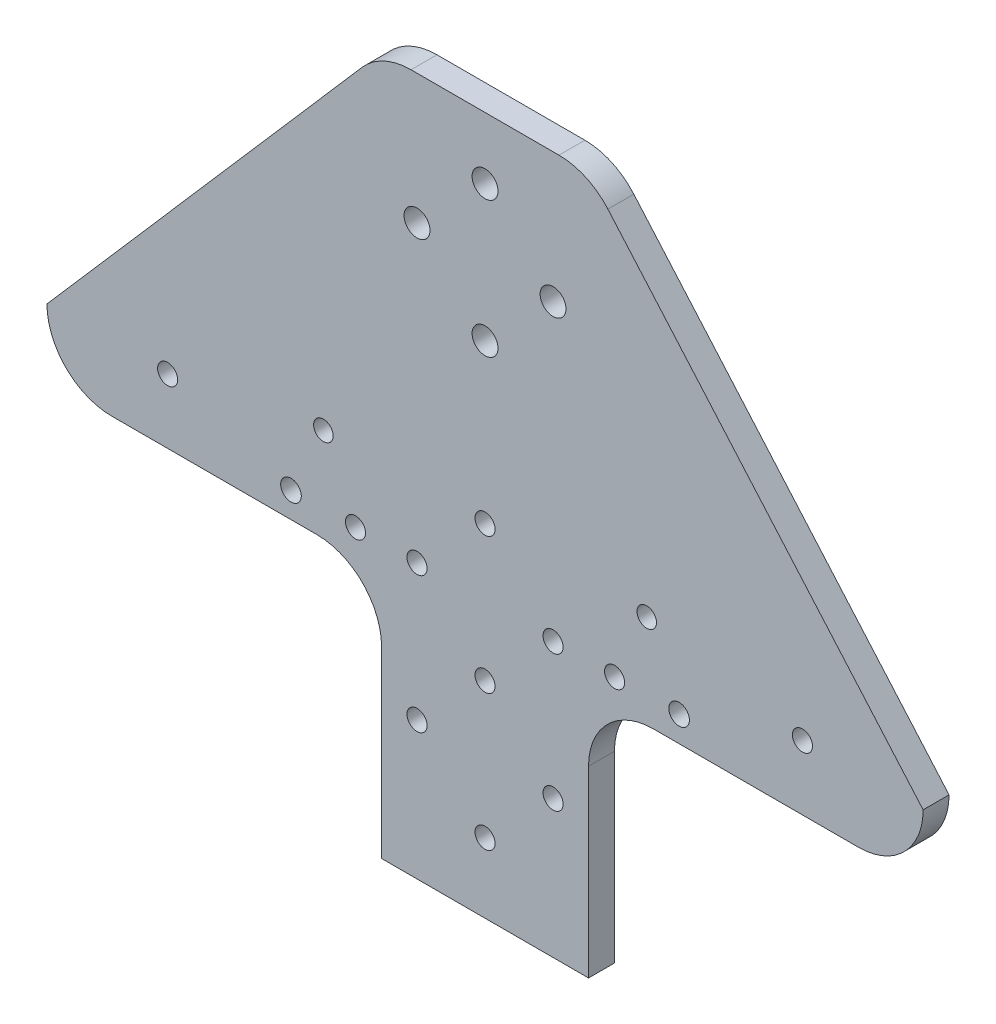
SolidWorks part; units mm, degrees
ref_plane "前视基准面" through (0, 0, 0) normal (0, 0, 1) x (1, 0, 0)
ref_plane "上视基准面" through (0, 0, 0) normal (0, 1, 0) x (1, 0, 0)
ref_plane "右视基准面" through (0, 0, 0) normal (1, 0, 0) x (0, 0, -1)
other "Configuration Table"
sketch "草图1" plane through (0, 0, 0) normal (0, 0, 1) x (1, 0, 0)
  line L1 (2.893, -14.1858) -> (-21.4145, -14.1858) construction
  line L2 (-16.4145, -3.6858) -> (9.0375, -3.6858) construction
  line L4 (-41.6823, -18.1278) -> (-17.4323, -18.1278)
  line L5 (-7.4323, -28.1278) -> (-7.4323, -56.4391)
  line L6 (-7.4323, -56.4391) -> (24.5197, -56.4391)
  line L7 (8.5437, -56.4391) -> (8.5437, 54.1049) construction
  line L13 (66.1735, -18.1278) -> (58.7697, -18.1278)
  line L18 (19.9627, 51.2868) -> (8.5437, 51.2868)
  line L20 (-131.4989, 1.4972) -> (-131.2303, 1.4972)
  line L21 (-41.6823, -18.1278) -> (-49.0861, -18.1278)
  line L24 (33.5019, -3.6858) -> (8.0499, -3.6858) construction
  line L25 (14.1944, -14.1858) -> (38.5019, -14.1858) construction
  line L26 (148.4506, 1.4972) -> (148.3177, 1.4972)
  line L29 (24.5197, -28.1278) -> (24.5197, -56.4391)
  line L30 (58.7697, -18.1278) -> (34.5197, -18.1278)
  line L33 (-59.0861, -8.1278) -> (-10.4221, 47.8478)
  line L34 (-2.8754, 51.2868) -> (8.5437, 51.2868)
  line L35 (76.1735, -8.1278) -> (27.5095, 47.8478)
  circle A0 centre (-40.4563, -8.1742) radius 1.55
  circle A1 centre (8.5437, 31.2637) radius 10.5 construction
  circle A2 centre (8.5437, 41.7637) radius 2
  circle A3 centre (19.0437, 31.2637) radius 2
  circle A4 centre (8.5437, 20.7637) radius 2
  circle A5 centre (-1.9563, 31.2637) radius 2
  arc A6 (-17.4323, -18.1278) -> (-7.4323, -28.1278) centre (-17.4323, -28.1278) cw
  arc A14 (9.913, -45.5639) -> (7.1743, -45.5639) centre (8.5437, -35.1858) cw construction
  circle A19 centre (8.5437, 31.2637) radius 10.5 construction
  circle A20 centre (-21.4145, -14.1858) radius 1.5934
  arc A23 (34.5197, -18.1278) -> (24.5197, -28.1278) centre (34.5197, -28.1278) ccw
  circle A24 centre (19.0437, 31.2637) radius 2
  circle A25 centre (8.5437, 20.7637) radius 2
  circle A26 centre (-1.9563, 31.2637) radius 2
  circle A27 centre (8.5437, 41.7637) radius 2
  circle A34 centre (8.5437, -24.6742) radius 1.5466
  arc A46 (-49.0861, -18.1278) -> (-59.0861, -8.1278) centre (-49.0861, -8.1278) cw
  arc A47 (76.1735, -8.1278) -> (66.1735, -18.1278) centre (66.1735, -8.1278) cw
  circle A50 centre (-11.4563, -14.1742) radius 1.55
  circle A51 centre (-1.9563, -14.1742) radius 1.55
  circle A52 centre (-16.4145, -3.6858) radius 1.5066
  circle A53 centre (8.5437, -3.6742) radius 1.55
  circle A54 centre (-1.9563, -35.1742) radius 1.55
  circle A55 centre (8.5437, -45.6742) radius 1.55
  circle A56 centre (19.0437, -35.1742) radius 1.55
  circle A57 centre (19.0437, -14.1742) radius 1.55
  circle A58 centre (28.5437, -14.1742) radius 1.55
  circle A59 centre (38.5019, -14.1858) radius 1.5934
  circle A60 centre (33.5019, -3.6858) radius 1.5066
  circle A61 centre (57.5437, -8.1742) radius 1.55
  arc A62 (27.5095, 47.8478) -> (19.9627, 51.2868) centre (19.9627, 41.2868) ccw
  arc A63 (-10.4221, 47.8478) -> (-2.8754, 51.2868) centre (-2.8754, 41.2868) cw
  point P2 (8.5437, 51.2868)
  point P13 (24.5197, 51.2868)
  point P59 (8.5437, 51.2868)
  point P61 (-7.4323, 51.2868)
  point P98 (-54.0861, -3.427)
  point P99 (8.5437, 6.8142)
  point P102 (-26.4145, -3.1858)
  point P109 (8.5437, 51.2868)
  point P118 (8.5437, 51.2868)
  point P119 (43.5019, -3.1858)
  point P120 (71.1735, -3.427)
  dimension "D1" = 21
  dimension "D2" = 4
  dimension "D3" = 10
  dimension "D4" = 10
  dimension "D8" = 28.3113
  dimension "D9" = 24.25
extrude "凸台-拉伸1" add sketch "草图1" along normal blind 4
